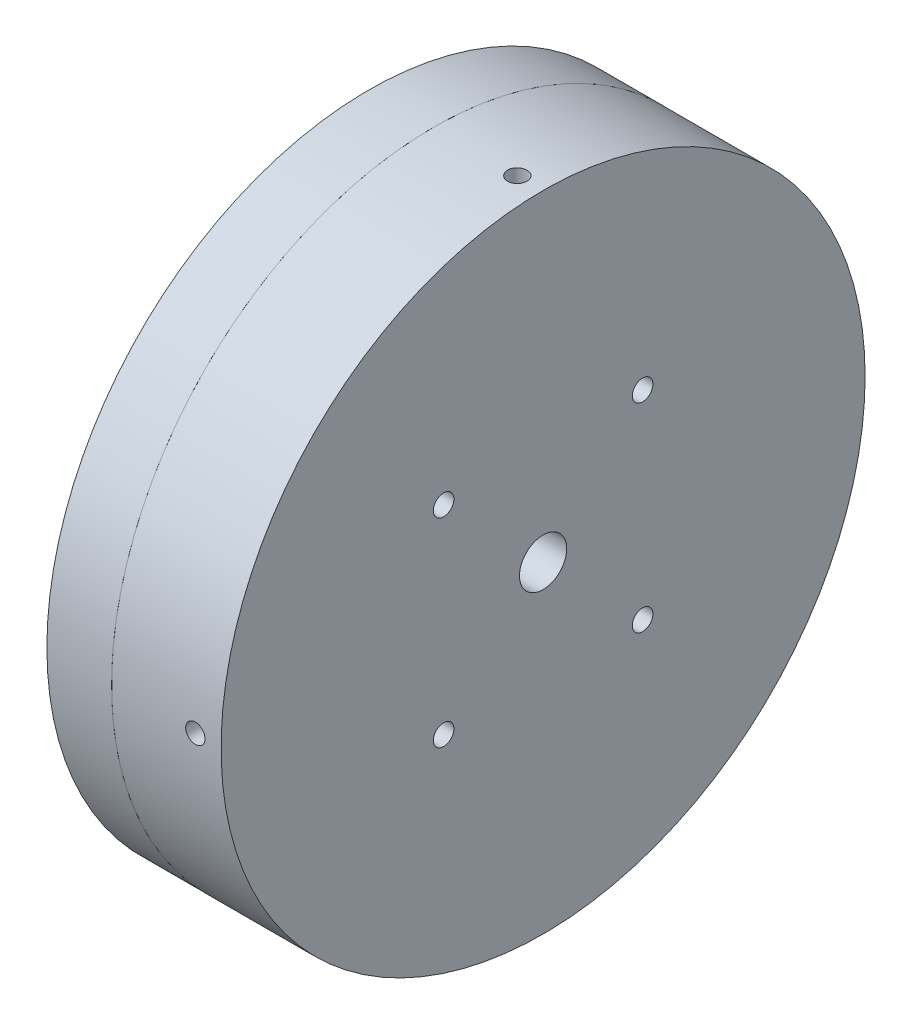
SolidWorks part; units mm, degrees
ref_plane "Plane1" through (0, 0, 0) normal (0, 0, 1) x (1, 0, 0)
ref_plane "Plane2" through (0, 0, 0) normal (0, 1, 0) x (1, 0, 0)
ref_plane "Plane3" through (0, 0, 0) normal (1, 0, 0) x (0, 0, -1)
other "Configuration Table"
sketch "HoldingSke" plane through (0, 0, 0) normal (0, 1, 0) x (1, 0, 0)
  line L0 (0, 0) -> (0.4377, -0.3673)
  line L1 (-15, 0) -> (100, 0) construction
  line L2 (0, 0) -> (-2.1039, 2.3779)
  line L3 (0, 0) -> (-11.863, 4.5341)
  line L4 (0, 0) -> (6.6156, 5.5511)
  line L5 (0, 0) -> (-23.7986, -8.8762)
  line L6 (0, 0) -> (-10.5278, -7.1032)
  line L7 (-2.1039, 2.3779) -> (3.3635, 27.1825)
  line L8 (-76.2, 4.1279) -> (-54.61, 4.1279)
  line L9 (-71.009, 38.7566) -> (-53.1078, 45.2721)
  line L10 (-76.2, 71.12) -> (104.1128, 71.12)
  line L11 (0, 0) -> (-10, 0)
  line L12 (-76.2, 101.6) -> (-76.147, 101.6)
  line L13 (24.9733, 27.94) -> (52.9518, 28.4284)
  line L14 (24.9733, 27.94) -> (24.9743, 27.94)
  line L15 (24.9733, 27.94) -> (100.4006, 29.5858)
  circle A0 centre (0, 0) radius 38.1
  circle A1 centre (0, 0) radius 12.7
  circle A2 centre (0, 0) radius 12.7
  dimension "MHD" = 25.4
  dimension "Hub_dia" = 25.4
  dimension "Diameter" = 76.2
  dimension "Num_teeth" = 40
  dimension "Pitch" = 0.5714
  dimension "Overall_len" = 25.4
  dimension "Show_teeth" = 40
  dimension "Thickness" = 12.7
  dimension "OAL" = 25.4001
  dimension "T_dim" = 21.59
  dimension "Ap" = 20
  dimension "H" = 19.05
  dimension "Pitch_radius" = 180.3128
  dimension "Width" = 10
  dimension "Backlash" = 0.053
  dimension "Addendum_fac" = 1
  dimension "Dedendum_fac" = 1.25
  dimension "Clearance_fac" = 0.25
  dimension "Dedendum_add" = 0.001
  dimension "Module" = 1.75
sketch "BasProSke" plane through (0, 0, 0) normal (0, 1, 0) x (1, 0, 0)
  line L0 (-10, 0) -> (60, 0) construction
  line L1 (0, 33.25) -> (0, 38.1)
  line L2 (0, 33.25) -> (10, 33.25)
  line L3 (10, 33.25) -> (10, 38.1)
  line L4 (10, 38.1) -> (0, 38.1)
  dimension "Diameter" = 76.2
  dimension "Thickness" = 10
  dimension "Inside_diameter" = 66.5
revolve "Base-Revolve" add sketch "BasProSke" angle 360 about L0
sketch "TooCutSke" plane through (0, 0, 0) normal (1, 0, 0) x (0, 0, -1)
  line L3 (1.5066, 34.9676) -> (1.5066, 53.6633) construction
  line L4 (0, 0) -> (0, 59.563) construction
  line L5 (0, 0) -> (-5.3609, 68.1169) construction
  line L6 (-14.7662, 28.5297) -> (35.4037, 32.4782) construction
  circle A0 centre (0, 0) radius 35 construction
  circle A1 centre (0, 0) radius 37.1885 construction
  circle A2 centre (0, 0) radius 29.6003 construction
  circle A3 centre (0, 0) radius 33.2246 construction
  arc A4 (2.1108, 33.1575) -> (0.443, 37.1859) centre (-14.7662, 28.5297) ccw
  arc A5 (2.1108, 33.1575) -> (-2.1108, 33.1575) centre (0, 0) ccw
  arc A6 (0.443, 37.1859) -> (-0.443, 37.1859) centre (0, 0) ccw
  arc A7 (-0.443, 37.1859) -> (-2.1108, 33.1575) centre (14.7662, 28.5297) ccw
  dimension "Pitch_dia" = 70
  dimension "Base_dia" = 59.2006
  dimension "Root_dia" = 74.377
  dimension "Overcut_dia" = 66.4492
  dimension "Flank_rad" = 17.5
  dimension "Half_ang" = 4.5
  dimension "Half_CT" = 1.5066
extrude "ToothCut" cut sketch "TooCutSke" along normal through all
fillet "Breaks" [suppressed] radius 0.175
fillet "RootFillets" [suppressed] radius 0.4385
pattern_circular "TeethCuts" count 40 over 360 about axis through (0, 0, 0) along (1, 0, 0) of "RootFillets", "Breaks", "ToothCut"
sketch "Sketch4" plane through (10, 0, 0) normal (1, 0, 0) x (0, 0, -1)
  circle A0 centre (0, 0) radius 50
  circle A1 centre (0, 0) radius 38.1
  dimension "D1" = 100
extrude "Boss-Extrude4" add sketch "Sketch4" against normal blind 10
sketch "Sketch5" plane through (0, 0, 0) normal (-1, 0, 0) x (0, 0, 1)
  circle A0 centre (0, 0) radius 40.7
  circle A1 centre (0, 0) radius 45
  circle A2 centre (0, 0) radius 50
  dimension "D1" = 81.4
  dimension "D2" = 90
  dimension "D3" = 100
sketch "Sketch12" plane through (10, 0, 0) normal (1, 0, 0) x (0, 0, -1)
  circle A0 centre (0, 0) radius 50
  dimension "D1" = 100
extrude "Boss-Extrude6" add sketch "Sketch12" along normal blind 7
sketch "Sketch13" plane through (10, 0, 0) normal (-1, 0, 0) x (0, 0, 1)
  circle A0 centre (0, 0) radius 37.1885
  dimension "D1" = 74.377
extrude "Cut-Extrude1" cut sketch "Sketch13" along normal blind 0.5
sketch "Sketch16" plane through (17, 0, 0) normal (1, 0, 0) x (0, 0, -1)
  circle A0 centre (0, 0) radius 3.67
  dimension "D1" = 7.34
extrude "Cut-Extrude2" cut sketch "Sketch16" against normal blind 20.5
ref_plane "Plane4" through (0, 32.2093, 8.2535) normal (0, 0.2482, -0.9687) x (-1, 0, 0)
extrude "Boss-Extrude7" add sketch "Sketch5" along normal blind 10.05 separate body contours A2 A0
ref_plane "Plane5" through (0, 50, 0) normal (0, 1, 0) x (1, 0, 0)
sketch "Sketch24" plane through (0, 50, 0) normal (0, 1, 0) x (1, 0, 0)
  circle A0 centre (13.0003, 0) radius 1.5
  dimension "D1" = 3
extrude "Cut-Extrude4" cut sketch "Sketch24" against normal blind 10
mirror "Mirror1" about plane through (0, 0, 0) normal (0, 1, 0) of "Cut-Extrude4"
pattern_circular "CirPattern1" count 2 every 90 about axis through (17, 0, 0) along (1, 0, 0) of "Mirror1", "Cut-Extrude4"
sketch "Sketch25" plane through (10, 0, 0) normal (-1, 0, 0) x (0, 0, 1)
  line L0 (0, 0) -> (-29.9489, 0) construction
  line L1 (-15.45, 15.45) -> (15.45, 15.45) construction
  line L2 (-15.45, 15.45) -> (-15.45, -15.45) construction
  line L3 (-15.45, -15.45) -> (15.45, -15.45) construction
  line L4 (15.45, 15.45) -> (15.45, -15.45) construction
  line L5 (-15.45, 15.45) -> (15.45, -15.45) construction
  line L6 (-15.45, -15.45) -> (15.45, 15.45) construction
  line L7 (0, 15.45) -> (0, -15.45) construction
  circle A0 centre (-15.45, 15.45) radius 1.6
  circle A1 centre (-15.45, -15.45) radius 1.6
  circle A2 centre (15.45, -15.45) radius 1.6
  circle A3 centre (15.45, 15.45) radius 1.6
  point P0 (0, 0)
  dimension "D3" = 3.2
  dimension "D1" = 30.9
  dimension "D2" = 30.9
extrude "Cut-Extrude5" cut sketch "Sketch25" against normal through all
equation "' \"Module@HoldingSke\" = 6.35"
equation "' \"Num_teeth@HoldingSke\" = 24"
equation "' \"Ap@HoldingSke\" =  14.5"
equation "' \"Ap@HoldingSke\" = 14.5"
equation "' \"Width@HoldingSke\" = 12"
equation "' \"Diameter@HoldingSke\" = 8 * 25.4"
equation "' \"Show_teeth@HoldingSke\" = 100"
equation "' \"Backlash@HoldingSke\" = 0.009 * 25.4"
equation "' \"Addendum_fac@HoldingSke\" = 1.0"
equation "' \"Dedendum_fac@HoldingSke\" = 1.25"
equation "' \"Dedendum_add@HoldingSke\" = 0.00005 * 25.4"
equation "' \"Clearance_fac@HoldingSke\" = 0.25"
equation "\"Pitch@HoldingSke\" = 1 / \"Module@HoldingSke\" "
equation "\"Overcut_dia@TooCutSke\" = (\"Num_teeth@HoldingSke\" - 2 * \"Addendum_fac@HoldingSke\") / \"Pitch@HoldingSke\" - 0.002 * 25.4"
equation "\"Pitch_dia@TooCutSke\" = \"Num_teeth@HoldingSke\" / \"Pitch@HoldingSke\""
equation "\"Base_dia@TooCutSke\" = \"Num_teeth@HoldingSke\" / \"Pitch@HoldingSke\" * cos((\"Ap@HoldingSke\"  * 3.14159265 / 180)) * 0.90"
equation "\"Root_dia@TooCutSke\" = \"Num_teeth@HoldingSke\"  / \"Pitch@HoldingSke\" + 2 *  \"Dedendum_fac@HoldingSke\"/ \"Pitch@HoldingSke\" + \"Dedendum_add@HoldingSke\" * 2"
equation "\"Half_ang@TooCutSke\" = 180 / \"Num_teeth@HoldingSke\""
equation "\"Half_CT@TooCutSke\" = \"Num_teeth@HoldingSke\" / \"Pitch@HoldingSke\" * sin((3.14159265 / 2 / \"Num_teeth@HoldingSke\")) / 2 + 10 * \"Backlash@HoldingSke\" / 4"
equation "\"Flank_rad@TooCutSke\" = \"Num_teeth@HoldingSke\" / \"Pitch@HoldingSke\" / 4"
equation "\"Radius@RootFillets\"= \"Clearance_fac@HoldingSke\" / \"Pitch@HoldingSke\" + \"Dedendum_add@HoldingSke\""
equation "\"Break_rad@Breaks\" = 0.02 / \"Pitch@HoldingSke\" * 5"
equation "\"Num_teeth@TeethCuts\" = int( \"Show_teeth@HoldingSke\" ) + 1"
equation "\"Num_teeth@TeethCuts\" = ((sgn( \"Num_teeth@TeethCuts\" - \"Num_teeth@HoldingSke\" )-1)*( \"Num_teeth@TeethCuts\" - \"Num_teeth@HoldingSke\" ))/-2+ \"Num_teeth@HoldingSke\""
equation "\"Num_teeth@TeethCuts\" = ((sgn( \"Num_teeth@TeethCuts\" - 2.0)+1)*( \"Num_teeth@TeethCuts\" - 2.0))/2 +2.0"
equation "\"Angle@TeethCuts\" = 360.0 / \"Num_teeth@HoldingSke\""
equation "\"Diameter@BasProSke\" = \"Num_teeth@HoldingSke\"  / \"Pitch@HoldingSke\" + 2 *  \"Dedendum_fac@HoldingSke\"/ \"Pitch@HoldingSke\" + \"Dedendum_add@HoldingSke\" * 2 + 0.002 * 25.4"
equation "\"Diameter@BasProSke\" = ((sgn( \"Diameter@BasProSke\"  - \"Diameter@HoldingSke\" )+1)*( \"Diameter@BasProSke\"  - \"Diameter@HoldingSke\" ))/2 + \"Diameter@HoldingSke\""
equation "\"Inside_diameter@BasProSke\" =  (\"Num_teeth@HoldingSke\" - 2 * \"Addendum_fac@HoldingSke\") / \"Pitch@HoldingSke\" "
equation "\"Thickness@BasProSke\"  = \"Width@HoldingSke\""
